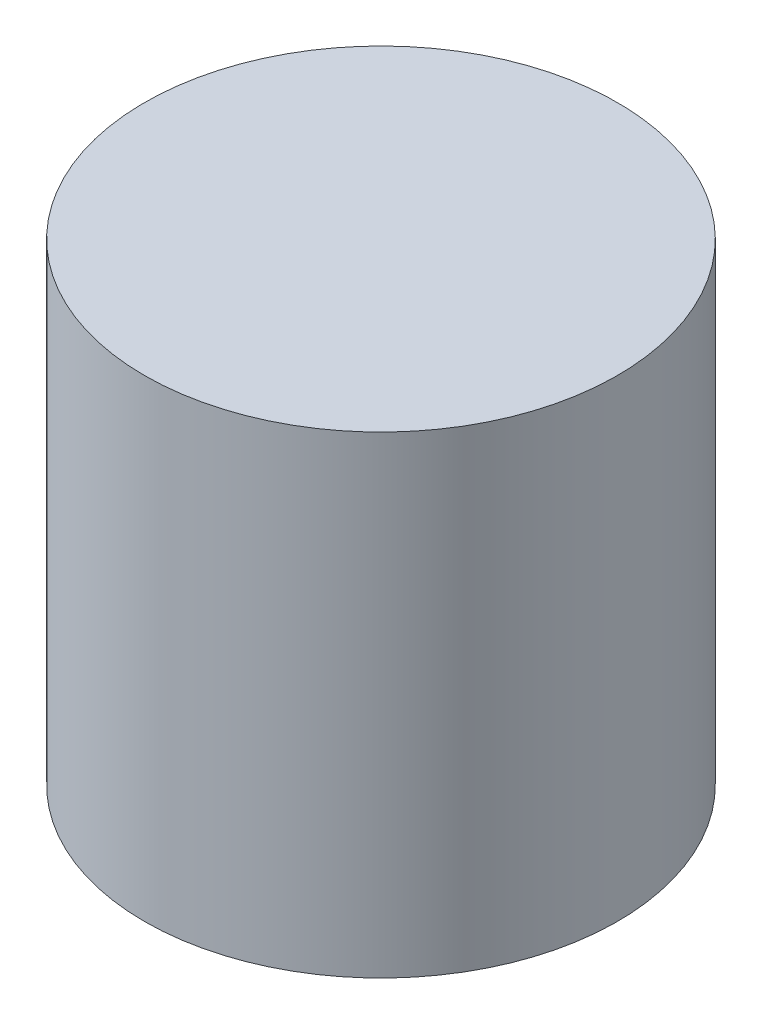
SolidWorks part; units mm, degrees
ref_plane "Front Plane" through (0, 0, 0) normal (0, 0, 1) x (1, 0, 0)
ref_plane "Top Plane" through (0, 0, 0) normal (0, 1, 0) x (1, 0, 0)
ref_plane "Right Plane" through (0, 0, 0) normal (1, 0, 0) x (0, 0, -1)
sketch "Sketch2" plane through (0, 0, 0) normal (0, 1, 0) x (1, 0, 0)
  circle A0 centre (0, 0) radius 1.5
  dimension "D1" = 3
extrude "Boss-Extrude1" add sketch "Sketch2" along normal blind 3
sketch "Sketch3" plane through (0, 3, 0) normal (0, 1, 0) x (1, 0, 0)
  point P0 (0, 0)
